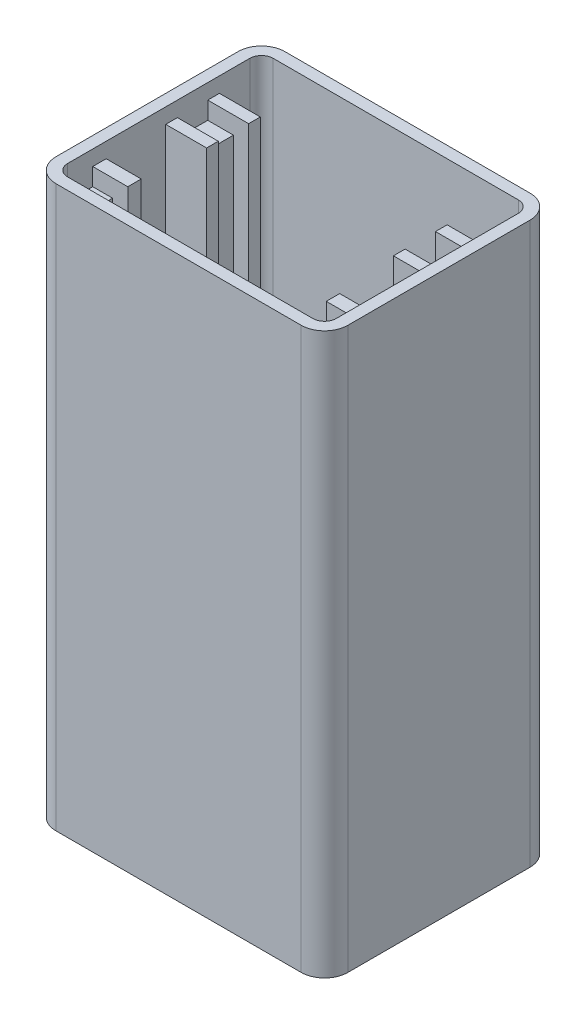
SolidWorks part; units mm, degrees
ref_plane "Спереди" through (0, 0, 0) normal (0, 0, 1) x (1, 0, 0)
ref_plane "Сверху" through (0, 0, 0) normal (0, 1, 0) x (1, 0, 0)
ref_plane "Справа" through (0, 0, 0) normal (1, 0, 0) x (0, 0, -1)
sketch "Эскиз1" plane through (0, 0, 0) normal (0, 1, 0) x (1, 0, 0)
  line L0 (-1.4532, 26.9688) -> (5.0068, 26.9688)
  line L1 (-1.4532, 26.5688) -> (5.0068, 26.5688) construction
  line L2 (-2.7232, 25.2988) -> (-2.7232, 24.6388) construction
  line L3 (-1.4532, 23.3688) -> (5.0068, 23.3688) construction
  line L4 (6.2768, 25.2988) -> (6.2768, 24.6388) construction
  line L5 (6.6768, 25.2988) -> (6.6768, 24.6388)
  line L6 (-1.4532, 22.9688) -> (5.0068, 22.9688)
  line L7 (-3.1232, 25.2988) -> (-3.1232, 24.6388)
  line L8 (0.7768, 21.4688) -> (0.7768, 22.9688)
  line L9 (0.7768, 22.9688) -> (1.7768, 22.9688)
  line L10 (-8.2232, 21.4688) -> (9.7768, 21.4688)
  line L11 (-8.2232, 23.2688) -> (-8.2232, 21.4688)
  line L12 (9.7768, 23.2688) -> (9.7768, 21.4688)
  line L13 (0.7768, 21.4688) -> (0.7768, 13.4688) construction
  line L14 (10.2768, 13.4688) -> (-8.7232, 13.4688) construction
  line L15 (0.7768, 11.6688) -> (0.7768, 9.6688) construction
  line L16 (-8.7232, 11.6688) -> (10.2768, 11.6688)
  line L17 (10.2768, 11.6688) -> (10.2768, 13.4688)
  line L18 (-8.7232, 13.4688) -> (-8.7232, 15.9688) construction
  line L19 (-8.7232, 15.9688) -> (-1.2232, 15.9688) construction
  line L20 (-8.7232, 11.6688) -> (-11.7232, 11.6688) construction
  line L21 (-11.7232, 11.6688) -> (-11.7232, 27.2688)
  line L22 (-9.7232, 9.6688) -> (9.2768, 9.6688)
  line L23 (10.2768, 11.6688) -> (13.2768, 11.6688) construction
  line L24 (9.2768, 9.6688) -> (11.2768, 9.6688)
  line L25 (-9.7232, 29.2688) -> (11.2768, 29.2688)
  line L26 (-2.4532, 27.2688) -> (-2.4532, 29.2688) construction
  line L27 (-8.7232, 13.4688) -> (-8.7232, 29.2688)
  line L28 (13.2768, 27.2688) -> (13.2768, 11.6688)
  line L29 (-4.9732, 15.9688) -> (0.7768, 15.9688) construction
  line L30 (6.5268, 15.9688) -> (5.0268, 15.9688) construction
  arc A0 (5.0068, 23.3688) -> (6.2768, 24.6388) centre (5.0068, 24.6388) ccw construction
  arc A1 (5.0068, 26.5688) -> (6.2768, 25.2988) centre (5.0068, 25.2988) cw construction
  arc A2 (-2.7232, 24.6388) -> (-1.4532, 23.3688) centre (-1.4532, 24.6388) ccw construction
  arc A3 (-1.4532, 26.5688) -> (-2.7232, 25.2988) centre (-1.4532, 25.2988) ccw construction
  arc A4 (5.0068, 26.9688) -> (6.6768, 25.2988) centre (5.0068, 25.2988) cw
  arc A5 (5.0068, 22.9688) -> (6.6768, 24.6388) centre (5.0068, 24.6388) ccw
  arc A6 (-3.1232, 24.6388) -> (-1.4532, 22.9688) centre (-1.4532, 24.6388) ccw
  arc A7 (-1.4532, 26.9688) -> (-3.1232, 25.2988) centre (-1.4532, 25.2988) ccw
  circle A8 centre (-4.9732, 15.9688) radius 2.5 construction
  arc A10 (-11.7232, 11.6688) -> (-9.7232, 9.6688) centre (-9.7232, 11.6688) ccw
  arc A11 (11.2768, 9.6688) -> (13.2768, 11.6688) centre (11.2768, 11.6688) ccw
  arc A12 (11.2768, 29.2688) -> (13.2768, 27.2688) centre (11.2768, 27.2688) cw
  arc A13 (-11.7232, 27.2688) -> (-9.7232, 29.2688) centre (-9.7232, 27.2688) cw
  circle A14 centre (5.0268, 15.9688) radius 2.9
  point P2 (5.0268, 15.9688)
  point P29 (1.7768, 22.9688)
  point P32 (0.7768, 21.4688)
  point P36 (0.7768, 13.4688)
  dimension "D1" = 1.27
  dimension "D9" = 2
  dimension "D4" = 3
  dimension "D5" = 3
  dimension "D6" = 1.8
  dimension "D7" = 1.8
  dimension "D8" = 2
extrude "Бобышка-Вытянуть3" add sketch "Эскиз1" along normal blind 1
sketch "Эскиз3" plane through (0, 1, 0) normal (0, 1, 0) x (1, 0, 0)
  line L0 (-0.4532, 26.2688) -> (6.0068, 26.2688)
  line L1 (-0.4532, 25.8688) -> (6.0068, 25.8688) construction
  line L2 (-1.7232, 24.5988) -> (-1.7232, 23.9388) construction
  line L3 (-0.4532, 22.6688) -> (6.0068, 22.6688) construction
  line L4 (7.2768, 24.5988) -> (7.2768, 23.9388) construction
  line L5 (7.6768, 24.5988) -> (7.6768, 23.9388)
  line L6 (-0.4532, 22.2688) -> (6.0068, 22.2688)
  line L7 (-2.1232, 24.5988) -> (-2.1232, 23.9388)
  line L8 (0.7768, 21.4688) -> (0.7768, 22.2688)
  line L9 (0.7768, 22.2688) -> (2.7768, 22.2688)
  line L10 (-8.2232, 21.4688) -> (9.7768, 21.4688)
  line L11 (-8.2232, 23.2688) -> (-8.2232, 21.4688) construction
  line L12 (9.7768, 23.2688) -> (9.7768, 21.4688)
  line L13 (0.7768, 21.4688) -> (0.7768, 13.4688) construction
  line L14 (10.2768, 13.4688) -> (-8.7232, 13.4688) construction
  line L15 (0.7768, 11.6688) -> (0.7768, 9.6688) construction
  line L16 (-8.7232, 11.6688) -> (10.2768, 11.6688)
  line L17 (10.2768, 11.6688) -> (10.2768, 13.4688)
  line L18 (10.4657, 14.9688) -> (11.6657, 14.9688)
  line L19 (-8.7232, 15.9688) -> (-1.2232, 15.9688) construction
  line L20 (-8.7232, 11.6688) -> (-11.7232, 11.6688) construction
  line L21 (-11.7232, 11.6688) -> (-11.7232, 27.2688)
  line L22 (-9.7232, 9.6688) -> (9.2768, 9.6688)
  line L23 (10.2768, 11.6688) -> (13.2768, 11.6688) construction
  line L24 (9.2768, 9.6688) -> (11.2768, 9.6688)
  line L25 (-9.7232, 29.2688) -> (11.2768, 29.2688)
  line L26 (-2.4532, 27.2688) -> (-2.4532, 29.2688) construction
  line L27 (-8.2232, 23.2688) -> (-7.2232, 23.2688) construction
  line L28 (13.2768, 27.2688) -> (13.2768, 11.6688)
  line L29 (-4.9732, 15.9688) -> (0.7768, 15.9688) construction
  line L30 (-7.2232, 23.2688) -> (-7.2232, 23.6688) construction
  line L31 (-7.2232, 23.6688) -> (-8.3636, 23.6688)
  line L32 (-8.5232, 23.6688) -> (-8.3636, 23.6688)
  line L33 (-8.2232, 21.0688) -> (-8.2232, 21.4688) construction
  line L34 (-8.5232, 23.6688) -> (-8.5232, 21.0688)
  line L35 (-8.5232, 21.0688) -> (-8.2232, 21.0688)
  line L36 (-8.2232, 21.0688) -> (-7.2232, 21.0688)
  line L37 (-7.2232, 21.0688) -> (-7.2232, 20.0688)
  line L38 (-7.2232, 20.0688) -> (-8.6636, 20.0688)
  line L39 (-8.6636, 20.0688) -> (-9.5232, 20.0688)
  line L40 (-7.2232, 23.6688) -> (-7.2232, 24.6688)
  line L41 (-7.2232, 24.6688) -> (-8.5232, 24.6688)
  line L42 (-8.5232, 24.6688) -> (-9.5232, 24.6688)
  line L43 (9.7768, 21.0688) -> (9.7768, 21.4688) construction
  line L44 (8.7768, 23.2688) -> (8.7768, 23.6688) construction
  line L45 (9.7768, 23.2688) -> (8.7768, 23.2688) construction
  line L46 (9.7768, 23.2688) -> (9.7768, 21.4688) construction
  line L47 (10.0768, 24.6688) -> (11.0768, 24.6688)
  line L48 (8.7768, 24.6688) -> (10.0768, 24.6688)
  line L49 (8.7768, 23.6688) -> (8.7768, 24.6688)
  line L50 (10.2171, 20.0688) -> (11.0768, 20.0688)
  line L51 (8.7768, 20.0688) -> (10.2171, 20.0688)
  line L52 (8.7768, 21.0688) -> (8.7768, 20.0688)
  line L53 (9.7768, 21.0688) -> (8.7768, 21.0688)
  line L54 (10.0768, 21.0688) -> (9.7768, 21.0688)
  line L55 (10.0768, 23.6688) -> (10.0768, 21.0688)
  line L56 (10.0768, 23.6688) -> (9.9171, 23.6688)
  line L57 (8.7768, 23.6688) -> (9.9171, 23.6688)
  line L58 (9.2768, 14.9688) -> (10.4657, 14.9688)
  line L59 (-8.7232, 13.8188) -> (-7.7232, 13.8188)
  line L60 (-7.7232, 13.8188) -> (-7.7232, 14.9688)
  line L61 (-8.7232, 13.8188) -> (-9.0232, 13.8188)
  line L62 (-7.7232, 14.9688) -> (-8.9122, 14.9688)
  line L63 (-8.9122, 14.9688) -> (-10.1122, 14.9688)
  line L64 (-8.7232, 11.6688) -> (-8.7232, 13.4688)
  line L65 (-8.7232, 12.5688) -> (-7.5713, 12.5688) construction
  line L66 (-8.7232, 11.3188) -> (-9.0232, 11.3188)
  line L67 (-8.9122, 10.1688) -> (-10.1122, 10.1688)
  line L68 (-7.7232, 10.1688) -> (-8.9122, 10.1688)
  line L69 (-7.7232, 11.3188) -> (-7.7232, 10.1688)
  line L70 (-8.7232, 11.3188) -> (-7.7232, 11.3188)
  line L71 (-9.0232, 11.3188) -> (-9.0232, 13.8188)
  line L72 (9.2768, 13.8188) -> (9.2768, 14.9688)
  line L73 (10.2768, 13.8188) -> (9.2768, 13.8188)
  line L74 (10.2768, 13.8188) -> (10.5768, 13.8188)
  line L75 (10.5768, 11.3188) -> (10.5768, 13.8188)
  line L76 (10.2768, 11.3188) -> (10.5768, 11.3188)
  line L77 (10.2768, 11.3188) -> (9.2768, 11.3188)
  line L78 (9.2768, 11.3188) -> (9.2768, 10.1688)
  line L79 (9.2768, 10.1688) -> (10.4657, 10.1688)
  line L80 (10.4657, 10.1688) -> (11.6657, 10.1688)
  line L81 (-9.7232, 28.2688) -> (11.2768, 28.2688)
  line L82 (12.2768, 27.2688) -> (12.2768, 11.6688)
  line L83 (9.2768, 10.6688) -> (11.2768, 10.6688)
  line L84 (-9.7232, 10.6688) -> (9.2768, 10.6688)
  line L85 (-10.7232, 11.6688) -> (-10.7232, 27.2688)
  line L86 (-10.1122, 14.9688) -> (-10.7232, 14.9688)
  line L87 (11.6657, 14.9688) -> (12.2768, 14.9688)
  line L88 (11.0768, 24.6688) -> (12.2768, 24.6688)
  line L89 (11.0768, 20.0688) -> (12.2768, 20.0688)
  line L90 (-9.5232, 24.6688) -> (-10.7232, 24.6688)
  line L91 (-9.5232, 20.0688) -> (-10.7232, 20.0688)
  line L92 (-9.5232, 20.0688) -> (-9.5232, 24.6688)
  line L93 (11.0768, 24.6688) -> (11.0768, 20.0688)
  line L94 (-9.0232, 12.5688) -> (-9.0232, 13.8188)
  arc A0 (6.0068, 22.6688) -> (7.2768, 23.9388) centre (6.0068, 23.9388) ccw construction
  arc A1 (6.0068, 25.8688) -> (7.2768, 24.5988) centre (6.0068, 24.5988) cw construction
  arc A2 (-1.7232, 23.9388) -> (-0.4532, 22.6688) centre (-0.4532, 23.9388) ccw construction
  arc A3 (-0.4532, 25.8688) -> (-1.7232, 24.5988) centre (-0.4532, 24.5988) ccw construction
  arc A4 (6.0068, 26.2688) -> (7.6768, 24.5988) centre (6.0068, 24.5988) cw
  arc A5 (6.0068, 22.2688) -> (7.6768, 23.9388) centre (6.0068, 23.9388) ccw
  arc A6 (-2.1232, 23.9388) -> (-0.4532, 22.2688) centre (-0.4532, 23.9388) ccw
  arc A7 (-0.4532, 26.2688) -> (-2.1232, 24.5988) centre (-0.4532, 24.5988) ccw
  circle A8 centre (-4.9732, 15.9688) radius 2.5 construction
  arc A9 (-11.7232, 11.6688) -> (-9.7232, 9.6688) centre (-9.7232, 11.6688) ccw
  arc A10 (11.2768, 9.6688) -> (13.2768, 11.6688) centre (11.2768, 11.6688) ccw
  arc A11 (11.2768, 29.2688) -> (13.2768, 27.2688) centre (11.2768, 27.2688) cw
  arc A12 (-11.7232, 27.2688) -> (-9.7232, 29.2688) centre (-9.7232, 27.2688) cw
  circle A13 centre (6.5268, 15.9688) radius 2.9
  arc A14 (11.2768, 28.2688) -> (12.2768, 27.2688) centre (11.2768, 27.2688) cw
  arc A15 (11.2768, 10.6688) -> (12.2768, 11.6688) centre (11.2768, 11.6688) ccw
  arc A16 (-10.7232, 11.6688) -> (-9.7232, 10.6688) centre (-9.7232, 11.6688) ccw
  arc A17 (-10.7232, 27.2688) -> (-9.7232, 28.2688) centre (-9.7232, 27.2688) cw
  point P6 (2.7768, 22.2688)
  point P9 (0.7768, 21.4688)
  point P13 (0.7768, 13.4688)
  point P66 (-9.7232, 29.2688)
  point P107 (-7.7232, 10.7438)
  point P117 (9.2768, 10.7438)
  point P136 (-9.0232, 12.5688)
  dimension "D1" = 1.27
  dimension "D7" = 2
  dimension "D2" = 3
  dimension "D3" = 1
  dimension "D4" = 1.8
  dimension "D5" = 1.8
  dimension "D6" = 2
extrude "Бобышка-Вытянуть6" add sketch "Эскиз3" along normal blind 47
sketch "Эскиз5" plane through (0, 48, 0) normal (0, 1, 0) x (1, 0, 0)
  line L0 (-10.7232, 28.2688) -> (12.2768, 10.6688) construction
  line L2 (-9.7232, 28.2688) -> (11.2768, 28.2688)
  line L3 (-10.7232, 27.2688) -> (-10.7232, 11.6688)
  line L4 (-9.7232, 10.6688) -> (11.2768, 10.6688)
  line L5 (12.2768, 27.2688) -> (12.2768, 11.6688)
  arc A0 (-10.7232, 11.6688) -> (-9.7232, 10.6688) centre (-9.7232, 11.6688) ccw
  arc A1 (11.2768, 10.6688) -> (12.2768, 11.6688) centre (11.2768, 11.6688) ccw
  arc A2 (11.2768, 28.2688) -> (12.2768, 27.2688) centre (11.2768, 27.2688) cw
  arc A3 (-9.7232, 28.2688) -> (-10.7232, 27.2688) centre (-9.7232, 27.2688) ccw
  dimension "D1" = 1
extrude "Вырез-Вытянуть1" cut sketch "Эскиз5" against normal blind 1.3
sketch "Эскиз6" plane through (0, 46.7, 0) normal (0, 1, 0) x (1, 0, 0)
  line L0 (-10.7232, 24.6688) -> (-10.7232, 20.0688) construction
  line L1 (-8.5232, 21.0688) -> (-10.7232, 21.0688)
  line L2 (-8.5232, 21.0688) -> (-8.5232, 23.6688)
  line L3 (-8.5232, 23.6688) -> (-10.7232, 23.6688)
  line L4 (-10.7232, 21.0688) -> (-10.7232, 23.6688)
  line L5 (-10.7232, 14.9688) -> (-10.7232, 11.6688) construction
  line L6 (-10.7232, 13.8188) -> (-10.7232, 11.6688)
  line L7 (-9.0232, 11.3188) -> (-9.0232, 13.8188)
  line L8 (-9.0232, 13.8188) -> (-10.7232, 13.8188)
  line L9 (-9.0232, 11.3188) -> (-10.66, 11.3188)
  line L10 (9.4461, 10.6688) -> (11.2768, 10.6688)
  line L11 (-7.8925, 10.6688) -> (-9.7232, 10.6688)
  line L12 (-9.7232, 10.6688) -> (-7.7232, 10.6688) construction
  line L13 (0.7768, 14.9688) -> (0.7768, 18.9393) construction
  line L14 (10.5768, 11.3188) -> (12.2135, 11.3188)
  line L15 (10.5768, 13.8188) -> (12.2768, 13.8188)
  line L16 (10.5768, 11.3188) -> (10.5768, 13.8188)
  line L17 (12.2768, 13.8188) -> (12.2768, 11.6688)
  line L18 (12.2768, 21.0688) -> (12.2768, 23.6688)
  line L19 (10.0768, 23.6688) -> (12.2768, 23.6688)
  line L20 (10.0768, 21.0688) -> (10.0768, 23.6688)
  line L21 (10.0768, 21.0688) -> (12.2768, 21.0688)
  arc A1 (-9.7232, 10.6688) -> (-10.7232, 11.6688) centre (-9.7232, 11.6688) cw
  arc A2 (11.2768, 10.6688) -> (12.2768, 11.6688) centre (11.2768, 11.6688) ccw
  line M3 (-8.5232, 21.0688) -> (-8.5232, 23.6688)
  line M7 (-10.7232, 24.6688) -> (-10.7232, 20.0688)
  dimension "D1" = 1
extrude "Вырез-Вытянуть2" cut sketch "Эскиз6" against normal blind 1.5 contours L3 L1 M3 M7 | L20 L21 L18 L19 | L14 A2 L17 L15 L16 | A1 L9 L7 L8 L6
sketch "Эскиз7" plane through (0, 0, 0) normal (0, -1, 0) x (1, 0, 0)
  line L0 (-11.1374, -10.2546) -> (12.691, -28.683) construction
  line L1 (-11.1374, -28.683) -> (12.691, -10.2546) construction
  arc A0 (-9.7232, -9.6688) -> (-11.7232, -11.6688) centre (-9.7232, -11.6688) ccw construction
  arc A1 (11.2768, -29.2688) -> (13.2768, -27.2688) centre (11.2768, -27.2688) ccw construction
  arc A2 (-11.7232, -27.2688) -> (-9.7232, -29.2688) centre (-9.7232, -27.2688) ccw construction
  arc A3 (13.2768, -11.6688) -> (11.2768, -9.6688) centre (11.2768, -11.6688) ccw construction
  circle A4 centre (5.0268, -15.9688) radius 2.9
